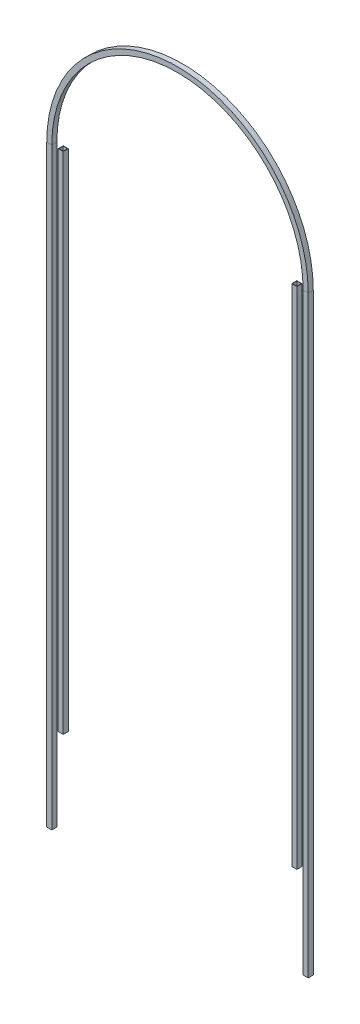
SolidWorks part; units mm, degrees
ref_plane "Front Plane" through (0, 0, 0) normal (0, 0, 1) x (1, 0, 0)
ref_plane "Top Plane" through (0, 0, 0) normal (0, 1, 0) x (1, 0, 0)
ref_plane "Right Plane" through (0, 0, 0) normal (1, 0, 0) x (0, 0, -1)
sketch "Sketch1" plane through (0, 0, 0) normal (0, 1, 0) x (1, 0, 0)
  line L0 (-17.5, -17.5) -> (-17.5, 17.5)
  line L1 (-20, -20) -> (20, -20)
  line L2 (-20, -20) -> (-20, 20)
  line L3 (-20, 20) -> (20, 20)
  line L4 (20, -20) -> (20, 20)
  line L5 (-20, -20) -> (20, 20) construction
  line L6 (-20, 20) -> (20, -20) construction
  line L7 (-17.5, 17.5) -> (17.5, 17.5)
  line L8 (17.5, -17.5) -> (17.5, 17.5)
  line L9 (-17.5, -17.5) -> (17.5, -17.5)
  point P0 (0, 0)
  dimension "D1" = 40
  dimension "D2" = 40
  dimension "D3" = 2.5
sketch "Sketch2" plane through (0, 0, 0) normal (0, 0, 1) x (1, 0, 0)
  line L0 (0, 0) -> (0, 4700)
  line L1 (2031.6408, 4700) -> (2031.6408, 0)
  arc A0 (0, 4700) -> (2031.6408, 4700) centre (1015.8204, 4700) cw
  dimension "D2" = 1015.8204
  dimension "D1" = 4700
  dimension "D3" = 4700
sweep "Sweep1" add profiles "Sketch1" path "Sketch2"
ref_plane "Plane2" through (0, 4700, 0) normal (0, 1, 0) x (1, 0, 0)
sketch "Sketch3" plane through (0, 4700, 0) normal (0, 1, 0) x (1, 0, 0)
  line L0 (20, -20) -> (20, 20) construction
  line L1 (70, 20.5551) -> (110, 20.5551)
  line L2 (70, 20.5551) -> (70, -19.4449)
  line L3 (70, -19.4449) -> (110, -19.4449)
  line L4 (110, 20.5551) -> (110, -19.4449)
  line L5 (70, 20.5551) -> (110, -19.4449) construction
  line L6 (70, -19.4449) -> (110, 20.5551) construction
  line L7 (72.5, 18.0551) -> (72.5, -16.9449)
  line L8 (72.5, -16.9449) -> (107.5, -16.9449)
  line L9 (107.5, 18.0551) -> (107.5, -16.9449)
  line L10 (72.5, 18.0551) -> (107.5, 18.0551)
  point P0 (90, 0.5551)
  dimension "D1" = 40
  dimension "D2" = 40
  dimension "D3" = 50
  dimension "D4" = 2.5
sketch "Sketch4" plane through (0, 0, 0) normal (0, 0, 1) x (1, 0, 0)
  line L0 (0, 4700) -> (90, 4700) construction
  line L2 (-20, 4700) -> (20, 4700) construction
  line L3 (90, 4700) -> (90, 700)
  dimension "D1" = 90
  dimension "D2" = 4000
sweep "Sweep2" add profiles "Sketch3" path "Sketch4"
sketch "Sketch10" plane through (0, 4700, 0) normal (0, -1, 0) x (1, 0, 0)
  line L0 (1959.1408, -17.5) -> (1959.1408, 17.5)
  line L1 (1961.6408, -20) -> (1921.6408, -20)
  line L2 (1961.6408, -20) -> (1961.6408, 20)
  line L3 (1961.6408, 20) -> (1921.6408, 20)
  line L4 (1921.6408, -20) -> (1921.6408, 20)
  line L5 (1961.6408, -20) -> (1921.6408, 20) construction
  line L6 (1961.6408, 20) -> (1921.6408, -20) construction
  line L7 (1959.1408, 17.5) -> (1924.1408, 17.5)
  line L8 (1924.1408, -17.5) -> (1924.1408, 17.5)
  line L9 (1959.1408, -17.5) -> (1924.1408, -17.5)
  line L10 (2011.6408, 20) -> (2011.6408, -20) construction
  point P0 (1941.6408, 0)
  dimension "D1" = 40
  dimension "D2" = 40
  dimension "D4" = 50
  dimension "D3" = 2.5
sketch "Sketch11" plane through (0, 0, 0) normal (0, 0, 1) x (1, 0, 0)
  line L0 (1941.6408, 4700) -> (1941.6408, 700)
  dimension "D1" = 4000
sweep "Sweep4" add profiles "Sketch10" path "Sketch11"
sketch "Sketch12" plane through (0, 0, 0) normal (0, 0, 1) x (1, 0, 0)
  line L0 (45, 500) -> (45, 4700)
  line L1 (1986.6408, 4700) -> (1986.6408, 500)
  line L2 (20, 0) -> (20, 4700) construction
  line L3 (70, 0) -> (70, 4700) construction
  line L4 (2011.6408, 4700) -> (2011.6408, 0) construction
  line L5 (1961.6408, 0) -> (1961.6408, 4700) construction
  arc A0 (45, 4700) -> (1986.6408, 4700) centre (1015.8204, 4700) cw
  arc A1 (1986.6408, 500) -> (45, 500) centre (1015.8204, 500) cw
  arc A2 (2011.6408, 4700) -> (20, 4700) centre (1015.8204, 4700) ccw construction
  dimension "D7" = 970.8204
  dimension "D1" = 25
  dimension "D2" = 25
  dimension "D3" = 25
  dimension "D4" = 25
  dimension "D5" = 25
  dimension "D8" = 25
  dimension "D9" = 25
  dimension "D10" = 25
  dimension "D11" = 25
  dimension "D6" = 4200
equation "\"C\"=4200"
equation "\"D6@Sketch12\"=\"C\""
